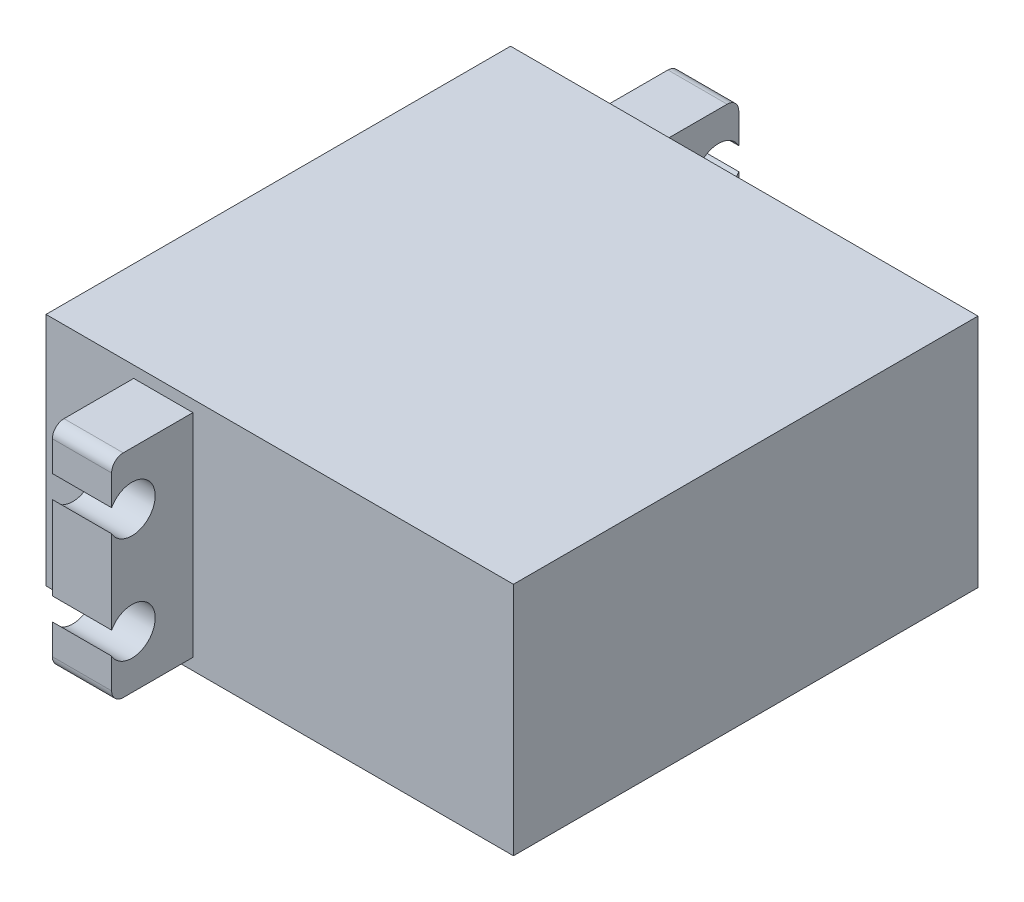
SolidWorks part; units mm, degrees
ref_plane "Front Plane" through (0, 0, 0) normal (0, 0, 1) x (1, 0, 0)
ref_plane "Top Plane" through (0, 0, 0) normal (0, 1, 0) x (1, 0, 0)
ref_plane "Right Plane" through (0, 0, 0) normal (1, 0, 0) x (0, 0, -1)
sketch "Sketch1" plane through (0, 0, 0) normal (0, 1, 0) x (1, 0, 0)
  line L0 (0, 0) -> (40.25, 0)
  line L1 (40.25, 0) -> (40.25, 40)
  line L2 (40.25, 40) -> (0, 40)
  line L3 (0, 40) -> (0, 0)
extrude "Boss-Extrude1" add sketch "Sketch1" along normal blind 20.25
sketch "Sketch2" plane through (0, 0, 0) normal (-1, 0, 0) x (0, 0, 1)
  line L0 (-40, 10.125) -> (0, 10.125) construction
  line L1 (-40, 20.25) -> (-40, 0) construction
  line L2 (0, 20.25) -> (0, 0) construction
  line L3 (0, 10.125) -> (-29.5, 10.125) construction
  circle A0 centre (-29.5, 10.125) radius 6.5
extrude "Boss-Extrude2" add sketch "Sketch2" along normal blind 1.35
sketch "Sketch3" plane through (-1.35, 0, 0) normal (-1, 0, 0) x (0, 0, 1)
  circle A0 centre (-29.5, 10.125) radius 3
extrude "Boss-Extrude3" add sketch "Sketch3" along normal blind 4.25
ref_plane "Plane1" through (12.65, 0, 0) normal (1, 0, 0) x (0, 0, -1)
sketch "Sketch4" plane through (12.65, 0, 0) normal (1, 0, 0) x (0, 0, -1)
  line L0 (20, 20.25) -> (20, 0) construction
  line L1 (0, 20.25) -> (40, 20.25) construction
  line L2 (0, 0) -> (40, 0) construction
  line L3 (40, 20.25) -> (40, 19.25) construction
  line L4 (40, 20.25) -> (40, 0) construction
  line L5 (40, 0) -> (40, 1) construction
  line L6 (40, 19.25) -> (46, 19.25)
  line L7 (47, 18.25) -> (47, 15.6557)
  line L8 (46, 1) -> (40, 1)
  line L9 (40, 19.25) -> (45.25, 19.25) construction
  line L10 (47, 13.7193) -> (47, 6.5307)
  line L11 (40, 10.125) -> (47, 10.125) construction
  line L12 (45.25, 10.125) -> (45.25, 19.25) construction
  line L13 (47, 4.5943) -> (47, 2)
  line L14 (40, 19.25) -> (40, 1)
  line L15 (0, 19.25) -> (-6, 19.25)
  line L16 (-7, 18.25) -> (-7, 15.6557)
  line L17 (-7, 13.7193) -> (-7, 6.5307)
  line L18 (-7, 4.5943) -> (-7, 2)
  line L19 (-6, 1) -> (0, 1)
  line L20 (0, 19.25) -> (0, 1)
  arc A0 (47, 15.6557) -> (47, 13.7193) centre (45.25, 14.6875) ccw
  arc A1 (47, 4.5943) -> (47, 6.5307) centre (45.25, 5.5625) cw
  arc A2 (47, 2) -> (46, 1) centre (46, 2) cw
  arc A3 (46, 19.25) -> (47, 18.25) centre (46, 18.25) cw
  arc A4 (-6, 19.25) -> (-7, 18.25) centre (-6, 18.25) ccw
  arc A5 (-7, 15.6557) -> (-7, 13.7193) centre (-5.25, 14.6875) cw
  arc A6 (-7, 4.5943) -> (-7, 6.5307) centre (-5.25, 5.5625) ccw
  arc A7 (-7, 2) -> (-6, 1) centre (-6, 2) ccw
  dimension "D2" = 1
  dimension "D1" = 5.25
extrude "Boss-Extrude4" add sketch "Sketch4" against normal blind 5.1
